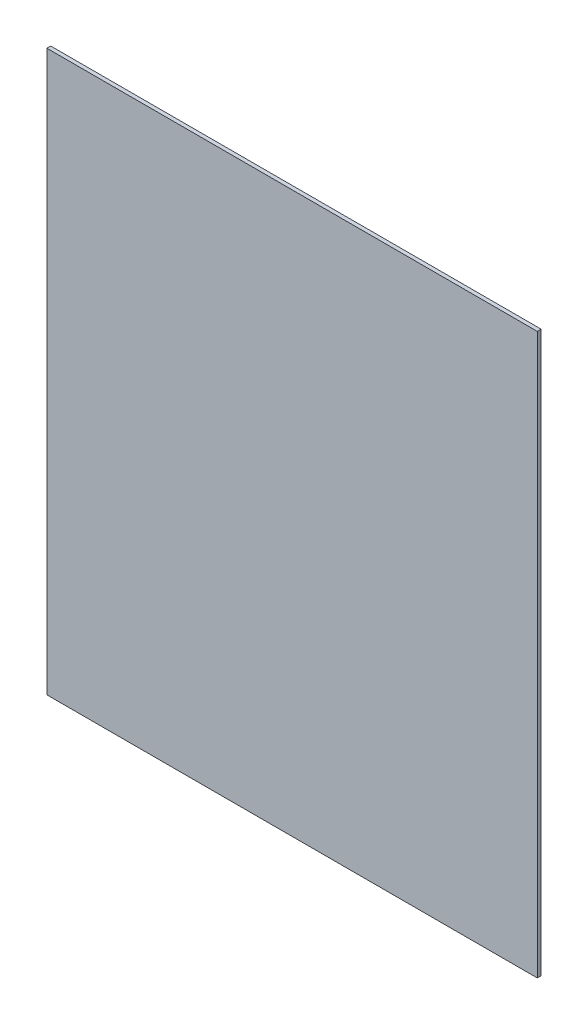
SolidWorks part; units mm, degrees
ref_plane "Plan de face" through (0, 0, 0) normal (0, 0, 1) x (1, 0, 0)
ref_plane "Plan de dessus" through (0, 0, 0) normal (0, 1, 0) x (1, 0, 0)
ref_plane "Plan de droite" through (0, 0, 0) normal (1, 0, 0) x (0, 0, -1)
sketch "Esquisse1" plane through (0, 0, 0) normal (0, 0, 1) x (1, 0, 0)
  line L1 (-416, -475) -> (416, -475)
  line L2 (-416, -475) -> (-416, 475)
  line L3 (-416, 475) -> (416, 475)
  line L4 (416, -475) -> (416, 475)
  line L5 (-416, -475) -> (416, 475) construction
  line L6 (-416, 475) -> (416, -475) construction
  point P0 (0, 0)
  dimension "D1" = 950
  dimension "D2" = 832
extrude "Boss.-Extru.1" add sketch "Esquisse1" along normal blind 6.5
